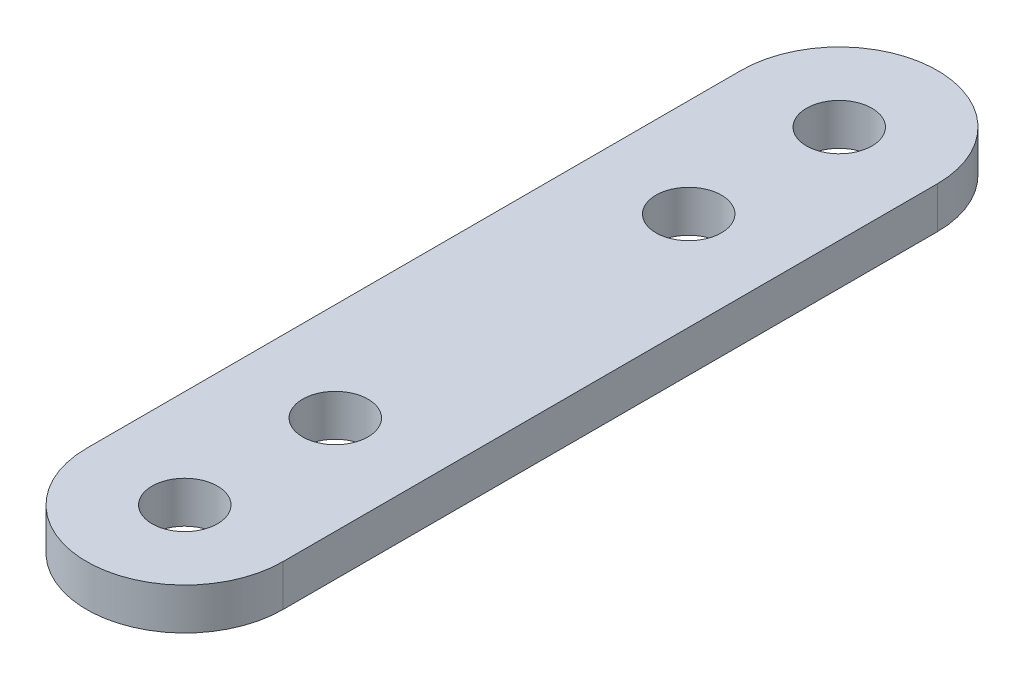
SolidWorks part; units mm, degrees
material "Acrylic (Medium-high impact)"
ref_plane "Front Plane" through (0, 0, 0) normal (0, 0, 1) x (1, 0, 0)
ref_plane "Top Plane" through (0, 0, 0) normal (0, 1, 0) x (1, 0, 0)
ref_plane "Right Plane" through (0, 0, 0) normal (1, 0, 0) x (0, 0, -1)
sketch "Sketch1" plane through (0, 0, 0) normal (0, 1, 0) x (1, 0, 0)
  line L0 (0, 13.5) -> (0, -13.5) construction
  line L1 (0, -25) -> (0, 25) construction
  line L2 (-7.5, 25) -> (-7.5, -25)
  line L3 (7.5, 25) -> (7.5, -25)
  circle A0 centre (0, 25) radius 2.5
  circle A1 centre (0, -25) radius 2.5
  circle A2 centre (0, 13.5) radius 2.5
  circle A3 centre (0, -13.5) radius 2.5
  arc A4 (-7.5, 25) -> (7.5, 25) centre (0, 25) cw
  arc A5 (-7.5, -25) -> (7.5, -25) centre (0, -25) ccw
  point P8 (0, 0)
  point P10 (0, 0)
  point P15 (0, 0)
  point P16 (0, -25.2144)
  point P17 (0, 0)
  dimension "D1" = 27
  dimension "D2" = 50
  dimension "D3" = 5
  dimension "D4" = 15
extrude "Boss-Extrude1" add sketch "Sketch1" along normal blind 3.175
